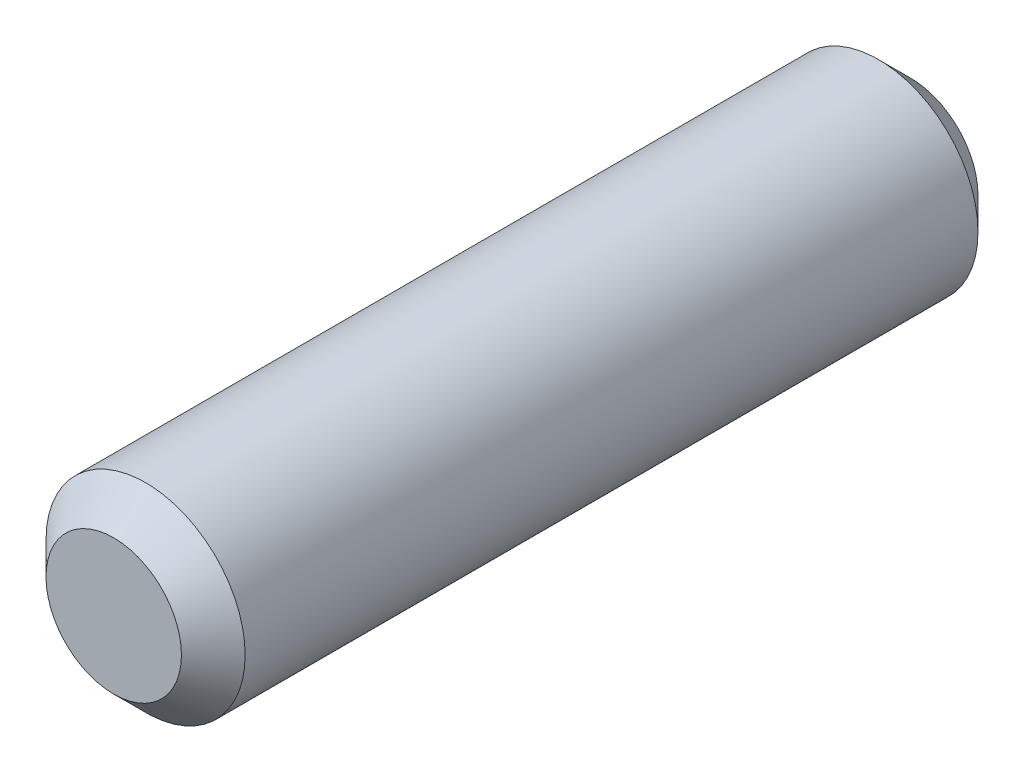
SolidWorks part; units mm, degrees
material "Alloy Steel"
ref_plane "Front Plane" through (0, 0, 0) normal (0, 0, 1) x (1, 0, 0)
ref_plane "Top Plane" through (0, 0, 0) normal (0, 1, 0) x (1, 0, 0)
ref_plane "Right Plane" through (0, 0, 0) normal (1, 0, 0) x (0, 0, -1)
sketch "Sketch1" plane through (0, 0, 0) normal (0, 0, 1) x (1, 0, 0)
  circle A0 centre (0, 0) radius 1.1906
  dimension "D1" = 2.3813
extrude "Boss-Extrude1" add sketch "Sketch1" along normal mid plane 9.525
chamfer "Chamfer1" distance 0.381 1 edges at (1.1906, 0, 4.7625)
chamfer "Chamfer2" distance 0.381 angle 45 1 edges at (1.1906, 0, -4.7625)
